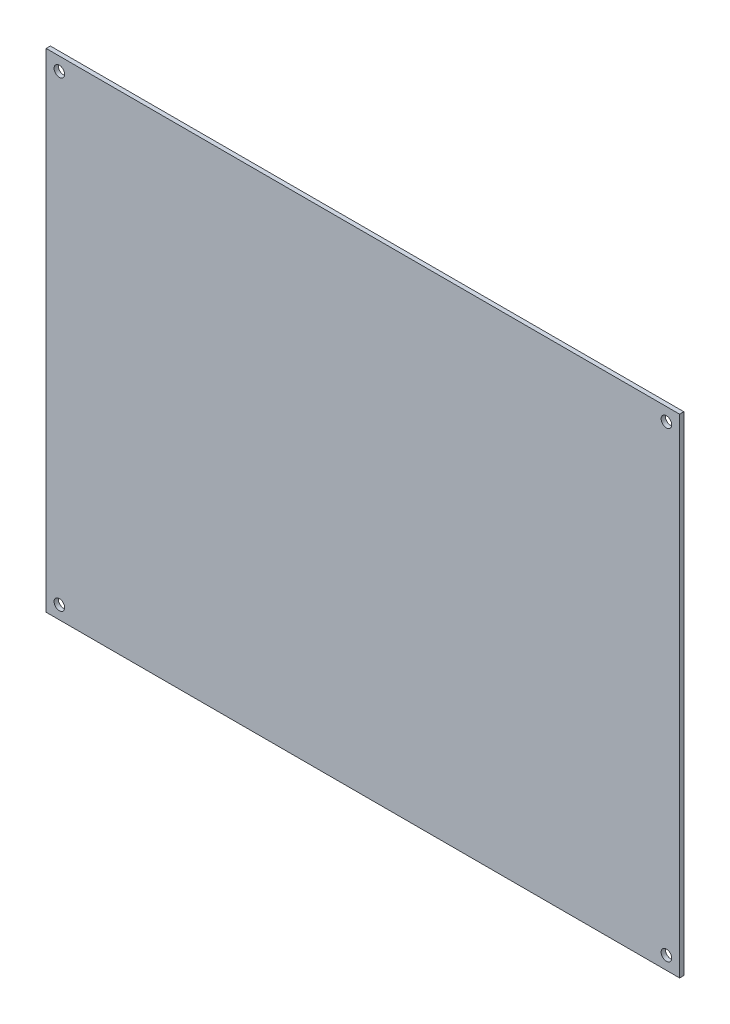
SolidWorks part; units mm, degrees
ref_plane "Front Plane" through (0, 0, 0) normal (0, 0, 1) x (1, 0, 0)
ref_plane "Top Plane" through (0, 0, 0) normal (0, 1, 0) x (1, 0, 0)
ref_plane "Right Plane" through (0, 0, 0) normal (1, 0, 0) x (0, 0, -1)
sketch "Sketch1" plane through (0, 0, 0) normal (0, 0, 1) x (1, 0, 0)
  line L0 (55, 0) -> (-55, 0) construction
  line L1 (-120, -92.5) -> (120, -92.5)
  line L2 (-120, -92.5) -> (-120, 92.5)
  line L3 (-120, 92.5) -> (120, 92.5)
  line L4 (120, -92.5) -> (120, 92.5)
  line L5 (-120, -92.5) -> (120, 92.5) construction
  line L6 (-120, 92.5) -> (120, -92.5) construction
  line L7 (0, -55) -> (0, 55) construction
  circle A0 centre (115, 87.5) radius 2
  circle A1 centre (115, -87.5) radius 2
  circle A2 centre (-115, -87.5) radius 2
  circle A3 centre (-115, 87.5) radius 2
  point P0 (0, 0)
  dimension "D5" = 4
  dimension "D1" = 185
  dimension "D2" = 240
  dimension "D3" = 5
  dimension "D4" = 5
extrude "Boss-Extrude1" add sketch "Sketch1" along normal blind 1.6
